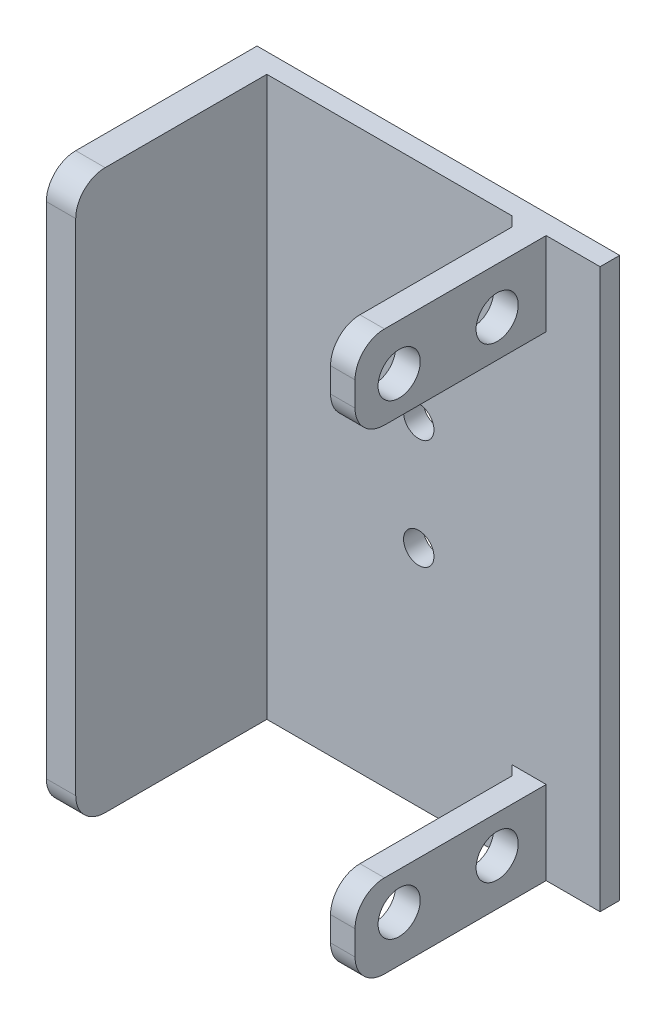
SolidWorks part; units mm, degrees
ref_plane "前视基准面" through (0, 0, 0) normal (0, 0, 1) x (1, 0, 0)
ref_plane "上视基准面" through (0, 0, 0) normal (0, 1, 0) x (1, 0, 0)
ref_plane "右视基准面" through (0, 0, 0) normal (1, 0, 0) x (0, 0, -1)
sketch "草图1" plane through (0, 0, 0) normal (0, 0, 1) x (1, 0, 0)
  line L1 (-18.5, 28.5) -> (18.5, 28.5)
  line L2 (-18.5, 28.5) -> (-18.5, -28.5)
  line L3 (-18.5, -28.5) -> (18.5, -28.5)
  line L4 (18.5, 28.5) -> (18.5, -28.5)
  line L5 (-18.5, 28.5) -> (18.5, -28.5) construction
  line L6 (-18.5, -28.5) -> (18.5, 28.5) construction
  point P0 (0, 0)
  dimension "D1" = 57
  dimension "D2" = 37
extrude "凸台-拉伸1" add sketch "草图1" along normal blind 2
sketch "草图2" plane through (0, 0, 2) normal (0, 0, 1) x (1, 0, 0)
  line L0 (-18.5, -28.5) -> (18.5, -28.5) construction
  line L1 (-18.5, 28.5) -> (-15.5, 28.5)
  line L2 (-18.5, 28.5) -> (-18.5, -28.5)
  line L3 (-18.5, -28.5) -> (-15.5, -28.5)
  line L4 (-15.5, 28.5) -> (-15.5, -28.5)
  dimension "D1" = 3
extrude "凸台-拉伸2" add sketch "草图2" along normal blind 19.5
sketch "草图3" plane through (0, 0, 2) normal (0, 0, 1) x (1, 0, 0)
  line L0 (13, -28.5) -> (13, -20)
  line L1 (-15.5, -28.5) -> (18.5, -28.5) construction
  line L2 (13, -20) -> (10.5, -20)
  line L3 (10.5, -20) -> (10.5, -28.5)
  line L4 (-15.5, -28.5) -> (-15.5, 28.5) construction
  line L5 (10.5, -28.5) -> (13, -28.5)
  line L6 (10.5, -20) -> (10.5, 20) construction
  line L7 (10.5, 20) -> (10.5, 28.5)
  line L8 (10.5, 28.5) -> (13, 28.5)
  line L9 (13, 28.5) -> (13, 20)
  line L10 (10.5, 20) -> (13, 20)
  dimension "D1" = 28.5
  dimension "D2" = 2.5
  dimension "D3" = 40
  dimension "D4" = 8.5
  dimension "D5" = 2.5
  dimension "D7" = 8.5
extrude "凸台-拉伸3" add sketch "草图3" along normal blind 19.5
sketch "草图4" plane through (0, 0, 2) normal (0, 0, 1) x (1, 0, 0)
  line L0 (0, 0) -> (0, -5.6)
  line L1 (0, 0) -> (-14.5, 0) construction
  circle A0 centre (0, -5.6) radius 1.55
  circle A1 centre (0, 5.6) radius 1.55
  dimension "D1" = 3.1
  dimension "D2" = 5.6
extrude "切除-拉伸1" cut sketch "草图4" against normal through all contours A1 | A0
sketch "草图6" plane through (-18.5, 0, 0) normal (-1, 0, 0) x (0, 0, 1)
  line L0 (21.5, -20) -> (2, -20) construction
  line L1 (21.5, -20) -> (2, -20) construction
  line L2 (11.5, -20) -> (11.5, -9.9) construction
  line L3 (21.5, 28.5) -> (21.5, -28.5) construction
  circle A0 centre (11.5, -9.9) radius 2.5
  dimension "D3" = 5
  dimension "D1" = 10.1
  dimension "D2" = 10
extrude "凸台-拉伸4" add sketch "草图6" along normal blind 3
sketch "草图7" plane through (13, 0, 0) normal (1, 0, 0) x (0, 0, -1)
  line L0 (-21.5, -28.5) -> (-21.5, -20) construction
  line L1 (0, 0) -> (-24.1864, 0) construction
  circle A0 centre (-17, -23.793) radius 2.15
  circle A1 centre (-7, -23.793) radius 2.15
  circle A2 centre (-7, 23.793) radius 2.15
  circle A3 centre (-17, 23.793) radius 2.15
  dimension "D1" = 4.5
  dimension "D2" = 4.3
  dimension "D3" = 10
extrude "切除-拉伸2" cut sketch "草图7" against normal blind 3
fillet "圆角1" radius 3 6 edges at (11.75, 28.5, 21.5) (11.75, -20, 21.5) (11.75, 20, 21.5) (11.75, -28.5, 21.5) (-17, -28.5, 21.5) (-17, 28.5, 21.5)
chamfer "倒角2" distance 1 angle 45 2 edges at (10.5, -24.25, 2) (10.5, 24.25, 2)
